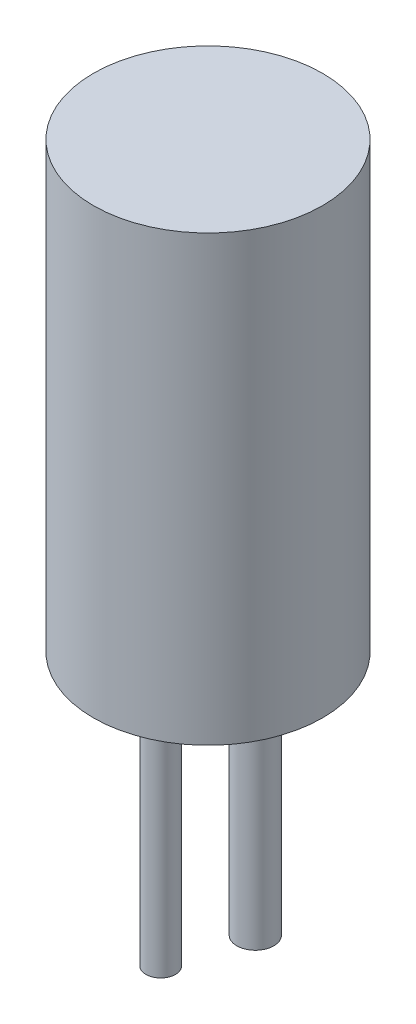
SolidWorks part; units mm, degrees
ref_plane "前视基准面" through (0, 0, 0) normal (0, 0, 1) x (1, 0, 0)
ref_plane "上视基准面" through (0, 0, 0) normal (0, 1, 0) x (1, 0, 0)
ref_plane "右视基准面" through (0, 0, 0) normal (1, 0, 0) x (0, 0, -1)
sketch "草图1" plane through (0, 0, 0) normal (0, 1, 0) x (1, 0, 0)
  circle A0 centre (0, 0) radius 3.1
  dimension "D1" = 6.2
extrude "拉伸1" add sketch "草图1" along normal blind 12
sketch "草图2" plane through (0, 0, 0) normal (0, -1, 0) x (1, 0, 0)
  line L0 (4.8023, 0) -> (-11.2367, 0) construction
  circle A0 centre (-1.28, 0) radius 0.4
  dimension "D2" = 0.8
  dimension "D1" = 1.28
extrude "拉伸2" add sketch "草图2" along normal blind 8
sketch "草图3" plane through (0, 0, 0) normal (0, -1, 0) x (1, 0, 0)
  line L0 (7.1249, 0) -> (-2.8562, 0) construction
  circle A0 centre (1.28, 0) radius 0.5
  dimension "D1" = 1
  dimension "D2" = 1.28
extrude "拉伸3" add sketch "草图3" along normal blind 6
